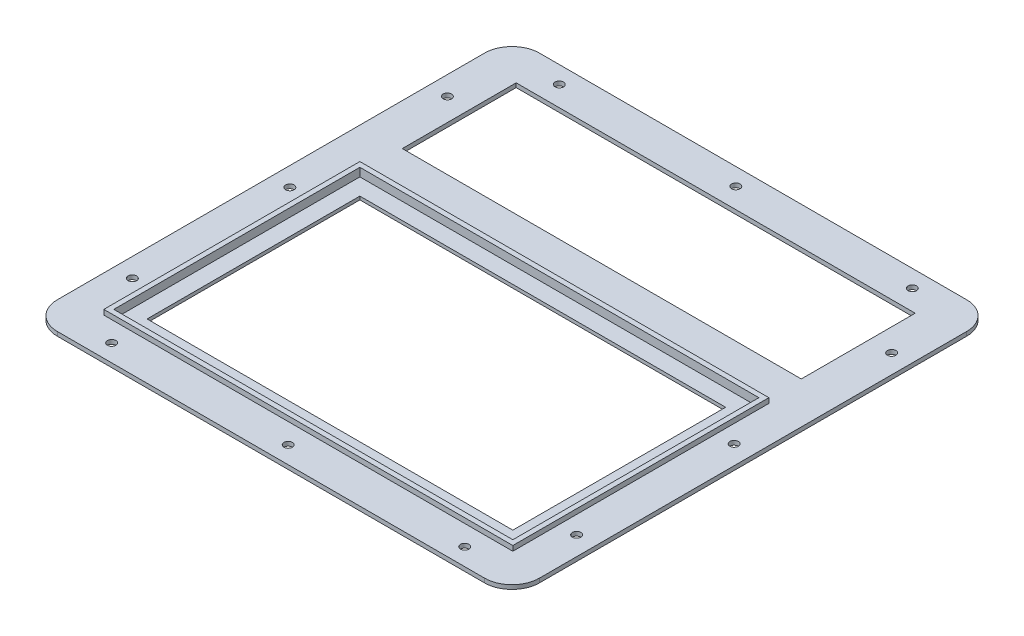
SolidWorks part; units mm, degrees
material "Alumina"
ref_plane "Front Plane" through (0, 0, 0) normal (0, 0, 1) x (1, 0, 0)
ref_plane "Top Plane" through (0, 0, 0) normal (0, 1, 0) x (1, 0, 0)
ref_plane "Right Plane" through (0, 0, 0) normal (1, 0, 0) x (0, 0, -1)
sketch "Sketch1" plane through (0, 0, 0) normal (0, 1, 0) x (1, 0, 0)
  line L1 (-123, -77) -> (123, -77)
  line L2 (-123, -77) -> (-123, 77)
  line L3 (-123, 77) -> (123, 77)
  line L4 (123, -77) -> (123, 77)
  line L5 (-123, -77) -> (123, 77) construction
  line L6 (-123, 77) -> (123, -77) construction
  point P0 (0, 0)
  dimension "D1" = 246
  dimension "D2" = 154
extrude "Boss-Extrude1" add sketch "Sketch1" against normal blind 7
sketch "Sketch2" plane through (0, 0, 0) normal (0, 1, 0) x (1, 0, 0)
  line L1 (-120, -74) -> (120, -74)
  line L2 (-120, -74) -> (-120, 74)
  line L3 (-120, 74) -> (120, 74)
  line L4 (120, -74) -> (120, 74)
  line L5 (-120, -74) -> (120, 74) construction
  line L6 (-120, 74) -> (120, -74) construction
  point P0 (0, 0)
  dimension "D1" = 240
  dimension "D2" = 148
extrude "Cut-Extrude1" cut sketch "Sketch2" against normal blind 5
sketch "Sketch3" plane through (0, -5, 0) normal (0, 1, 0) x (1, 0, 0)
  line L0 (120, 74) -> (-120, 74) construction
  line L1 (-110, -64) -> (110, -64)
  line L2 (-110, -64) -> (-110, 64)
  line L3 (-110, 64) -> (110, 64)
  line L4 (110, -64) -> (110, 64)
  line L5 (-110, -64) -> (110, 64) construction
  line L6 (-110, 64) -> (110, -64) construction
  line L7 (-120, 74) -> (-120, -74) construction
  point P0 (0, 0)
  point P8 (0, 0)
  dimension "D1" = 10
  dimension "D2" = 10
extrude "Cut-Extrude2" cut sketch "Sketch3" against normal blind 5
sketch "Sketch6" plane through (0, 0, 0) normal (0, 1, 0) x (1, 0, 0)
  line L0 (-120, 168) -> (-120, 99.5)
  line L1 (-128.49, -99.5) -> (128.49, -99.5)
  line L5 (-123, -77) -> (123, -77) construction
  line L6 (-120, 99.5) -> (120, 99.5)
  line L7 (120, 99.5) -> (120, 168)
  line L8 (-145, -82.99) -> (-145, 173.99)
  line L13 (123, -77) -> (123, 77) construction
  line L14 (-123, 77) -> (-123, -77) construction
  line L16 (145, 173.99) -> (145, -82.99)
  line L17 (123, -77) -> (123, 77)
  line L19 (123, 77) -> (-123, 77) construction
  line L20 (-123, -77) -> (123, -77)
  line L21 (-123, 77) -> (-123, -77)
  line L22 (123, 77) -> (-123, 77)
  line L23 (-120, 168) -> (120, 168)
  line L24 (-128.49, 190.5) -> (128.49, 190.5)
  arc A4 (128.49, 190.5) -> (145, 173.99) centre (128.49, 173.99) cw
  arc A5 (-145, 173.99) -> (-128.49, 190.5) centre (-128.49, 173.99) cw
  arc A6 (-128.49, -99.5) -> (-145, -82.99) centre (-128.49, -82.99) cw
  arc A7 (128.49, -99.5) -> (145, -82.99) centre (128.49, -82.99) ccw
  point P0 (0, 0)
  point P2 (0, -99.5)
  point P9 (130.775, 190.1075)
  point P16 (-126.8001, 190.5)
  point P21 (0, 0)
  point P24 (0, 0)
  point P26 (-145.5, 190.5)
  point P28 (0, 0)
  dimension "D3" = 22
  dimension "D1" = 16.51
  dimension "D7" = 25
  dimension "D10" = 99.5
  dimension "D9" = 16.51
  dimension "D11" = 22.5
  dimension "D2" = 22.5
  dimension "D5" = 22.5
  dimension "D6" = 290
  dimension "D8" = 25
  dimension "D12" = 290
extrude "Boss-Extrude2" add sketch "Sketch6" against normal blind 2.5 from offset 3 offset against normal yes
sketch "Sketch8" plane through (0, -5, 0) normal (0, 1, 0) x (1, 0, 0)
  line L0 (-120, -74) -> (120, -74) construction
  line L1 (-19, -73.1) -> (20, -73.1)
  line L2 (-19, -73.1) -> (-19, -72.8)
  line L3 (-19, -72.8) -> (20, -72.8)
  line L4 (20, -73.1) -> (20, -72.8)
  line L5 (-19, -73.1) -> (20, -72.8) construction
  line L6 (-19, -72.8) -> (20, -73.1) construction
  line L8 (-42.26, -73.1) -> (-30, -73.1)
  line L9 (-42.26, -73.1) -> (-42.26, -72.8)
  line L10 (-42.26, -72.8) -> (-30, -72.8)
  line L11 (-30, -73.1) -> (-30, -72.8)
  line L12 (-42.26, -73.1) -> (-30, -72.8) construction
  line L13 (-42.26, -72.8) -> (-30, -73.1) construction
  point P0 (0.5, -72.95)
  point P7 (-36.13, -72.95)
  point P13 (0, 0)
  point P14 (0, 0)
  point P15 (0, 0)
  dimension "D1" = 19
  dimension "D2" = 20
  dimension "D3" = 0.3
  dimension "D4" = 0.9
  dimension "D5" = 12.26
  dimension "D6" = 30
extrude "Cut-Extrude5" cut sketch "Sketch8" against normal blind 5
sketch "Sketch9" plane through (0, -5, 0) normal (0, 1, 0) x (1, 0, 0)
  line L4 (-120, -74) -> (120, -74) construction
  line L5 (120, -74) -> (120, 74) construction
  circle A0 centre (119, -46.2) radius 0.5
  circle A1 centre (119, -42.7) radius 0.5
  point P4 (0, 0)
  point P5 (0, 0)
  point P6 (113.6088, -35.586)
  dimension "D1" = 1
  dimension "D2" = 1
  dimension "D3" = 27.8
  dimension "D4" = 31.3
extrude "Cut-Extrude6" cut sketch "Sketch9" against normal blind 5
sketch "Sketch10" plane through (0, -3, 0) normal (0, 1, 0) x (1, 0, 0)
  line L0 (0, 157.1305) -> (0, -54.124) construction
  line L1 (-84.5431, 45.5) -> (100.6663, 45.5) construction
  line L2 (145, -82.99) -> (145, 173.99) construction
  circle A0 centre (-133.604, 140.242) radius 2.54
  circle A1 centre (-106.172, 180.12) radius 2.54
  circle A2 centre (-133.604, -49.242) radius 2.54
  circle A3 centre (-133.604, 45.5) radius 2.54
  circle A4 centre (0, 180.12) radius 2.54
  circle A5 centre (0, -89.12) radius 2.54
  circle A6 centre (-106.172, -89.12) radius 2.54
  circle A7 centre (106.172, -89.12) radius 2.54
  circle A8 centre (133.604, 45.5) radius 2.54
  circle A9 centre (133.604, -49.242) radius 2.54
  circle A10 centre (106.172, 180.12) radius 2.54
  circle A11 centre (133.604, 140.242) radius 2.54
  point P29 (145, 45.5)
  dimension "D3" = 5.08
  dimension "D1" = 94.742
  dimension "D2" = 133.604
  dimension "D4" = 134.62
  dimension "D5" = 106.172
  dimension "D6" = 45.5
extrude "Cut-Extrude7" cut sketch "Sketch10" against normal blind 5
